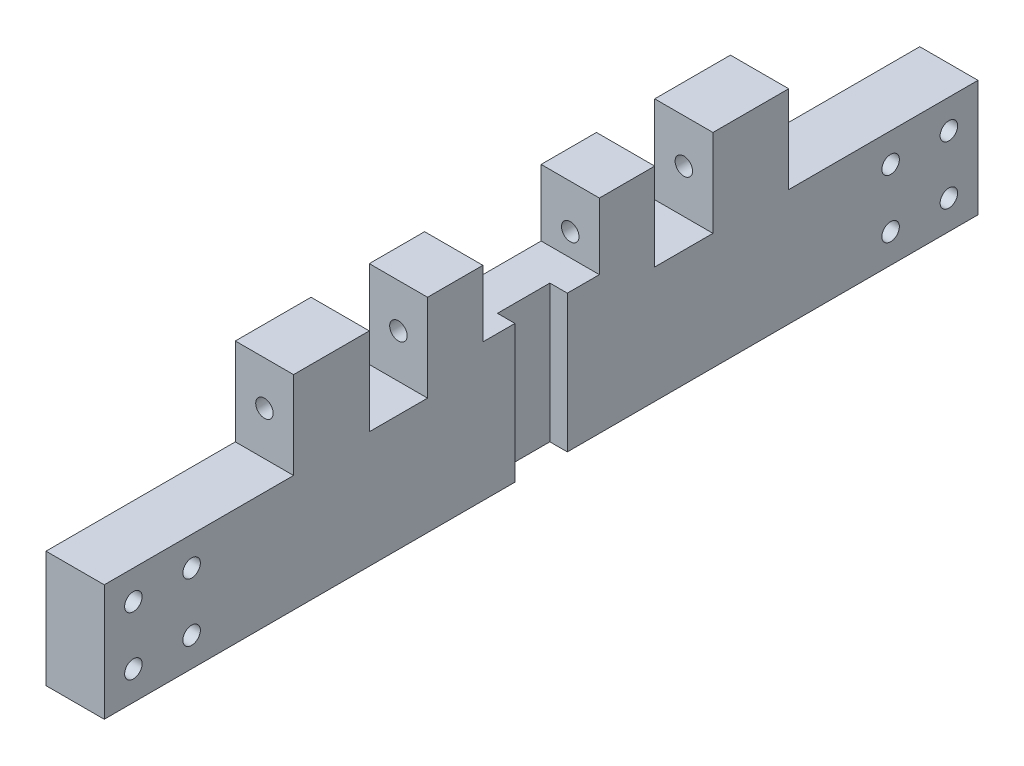
SolidWorks part; units mm, degrees
ref_plane "前视基准面" through (0, 0, 0) normal (0, 0, 1) x (1, 0, 0)
ref_plane "上视基准面" through (0, 0, 0) normal (0, 1, 0) x (1, 0, 0)
ref_plane "右视基准面" through (0, 0, 0) normal (1, 0, 0) x (0, 0, -1)
sketch "草图1" plane through (0, 0, 0) normal (1, 0, 0) x (0, 0, -1)
  line L1 (-10, -15) -> (10, -15)
  line L2 (-10, -15) -> (-10, 15)
  line L3 (-10, 15) -> (10, 15)
  line L4 (10, -15) -> (10, 15)
  line L5 (-10, -15) -> (10, 15) construction
  line L6 (-10, 15) -> (10, -15) construction
  point P0 (0, 0)
  dimension "D1" = 30
  dimension "D2" = 20
extrude "凸台-拉伸1" add sketch "草图1" along normal blind 10
sketch "草图3" plane through (0, 0, -10) normal (0, 0, -1) x (-1, 0, 0)
  line L0 (0, -15) -> (0, 15) construction
  line L1 (0, 11.3899) -> (-10, 11.3899)
  line L2 (0, 11.3899) -> (0, -8.6101)
  line L3 (0, -8.6101) -> (-10, -8.6101)
  line L4 (-10, 11.3899) -> (-10, -8.6101)
  dimension "D1" = 10
  dimension "D2" = 20
extrude "凸台-拉伸2" add sketch "草图3" along normal blind 65
mirror "镜向1" about plane through (0, 0, 0) normal (0, 0, 1) of "凸台-拉伸2"
sketch "草图4" plane through (10, 0, 0) normal (1, 0, 0) x (0, 0, -1)
  circle A0 centre (-70, 6.3899) radius 1.5
  circle A1 centre (-60, 6.3899) radius 1.5
  circle A2 centre (-70, -3.6101) radius 1.5
  circle A3 centre (-60, -3.6101) radius 1.5
  dimension "D1" = 3
  dimension "D2" = 3
  dimension "D3" = 3
  dimension "D4" = 3
extrude "切除-拉伸1" cut sketch "草图4" against normal through all
mirror "镜向2" about plane through (0, 0, 0) normal (0, 0, 1) of "切除-拉伸1"
sketch "草图5" plane through (10, 0, 0) normal (1, 0, 0) x (0, 0, -1)
  line L0 (-10, -15) -> (10, -15) construction
  line L1 (-4.5, 15) -> (4.5, 15)
  line L2 (-4.5, 15) -> (-4.5, -15)
  line L3 (-4.5, -15) -> (4.5, -15)
  line L4 (4.5, 15) -> (4.5, -15)
  line L5 (-4.5, 15) -> (4.5, -15) construction
  line L6 (-4.5, -15) -> (4.5, 15) construction
  point P0 (0, 0)
  dimension "D1" = 9
extrude "切除-拉伸2" cut sketch "草图5" against normal blind 3
sketch "草图6" plane through (10, 0, 0) normal (1, 0, 0) x (0, 0, -1)
  line L1 (19.5, 11.3899) -> (29.5, 11.3899)
  line L2 (19.5, 11.3899) -> (19.5, 1.3899)
  line L3 (19.5, 1.3899) -> (29.5, 1.3899)
  line L4 (29.5, 11.3899) -> (29.5, 1.3899)
  line L5 (19.5, 11.3899) -> (29.5, 1.3899) construction
  line L6 (19.5, 1.3899) -> (29.5, 11.3899) construction
  line L7 (-75, 11.3899) -> (-75, -8.6101) construction
  line L11 (75, 11.3899) -> (10, 11.3899) construction
  line L13 (19.5, 11.3899) -> (19.5, 26.3899)
  line L14 (10, 26.3899) -> (19.5, 26.3899)
  line L19 (19.5, 11.3899) -> (10, 11.3899)
  line L20 (10, 11.3899) -> (10, 26.3899)
  line L21 (29.5, 11.3899) -> (42.5, 11.3899)
  line L22 (75, 11.3899) -> (10, 11.3899) construction
  line L23 (42.5, 11.3899) -> (42.5, 26.3899)
  line L24 (42.5, 26.3899) -> (29.5, 26.3899)
  line L25 (29.5, 26.3899) -> (29.5, 11.3899)
  point P0 (24.5, 6.3899)
  line M15 (75, 11.3899) -> (10, 11.3899)
  line M16 (10, 11.3899) -> (10, 15)
  dimension "D1" = 10
  dimension "D2" = 94.5
  dimension "D3" = 10
  dimension "D4" = 15
extrude "凸台-拉伸3" add sketch "草图6" along direction (-1, 0, 0) on the side against the normal up to surface (10 mm away) contours L24 L25 L23 M15 | L20 L13 L14 M16 M15
sketch "草图7" plane through (0, 0, -42.5) normal (0, 0, -1) x (-1, 0, 0)
  line L0 (0, 11.3899) -> (0, 26.3899) construction
  line L1 (0, 26.3899) -> (-10, 26.3899) construction
  circle A0 centre (-5, 18.8899) radius 1.5
  dimension "D1" = 3
  dimension "D2" = 5
  dimension "D3" = 7.5
extrude "切除-拉伸5" cut sketch "草图7" against normal through all
mirror "镜向4" about plane through (0, 0, 0) normal (0, 0, 1) of "凸台-拉伸3", "切除-拉伸5"
sketch "草图8" plane through (0, -15, 0) normal (0, -1, 0) x (1, 0, 0)
  line L1 (-10, -10) -> (10, -10)
  line L2 (-10, -10) -> (-10, 10)
  line L3 (-10, 10) -> (10, 10)
  line L4 (10, -10) -> (10, 10)
  line L5 (-10, -10) -> (10, 10) construction
  line L6 (-10, 10) -> (10, -10) construction
  line L7 (10, 10) -> (10, 4.5) construction
extrude "切除-拉伸6" cut sketch "草图8" against normal up to surface (6.3899 mm away) up to face at (5, -8.6101, 42.5)
